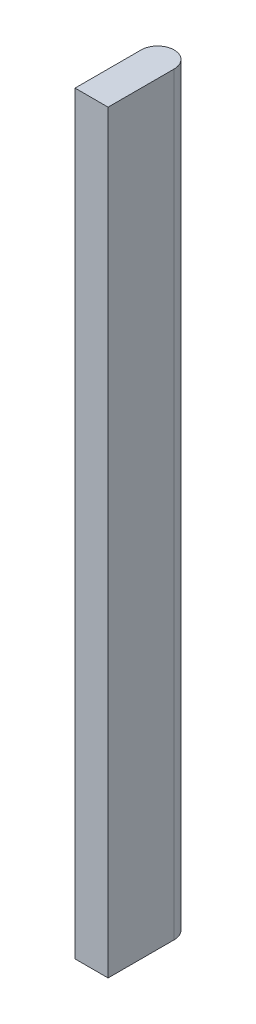
SolidWorks part; units mm, degrees
material "Delrin 2700 NC010, Low Viscosity Acetal Copolymer (SS)"
ref_plane "Front Plane" through (0, 0, 0) normal (0, 0, 1) x (1, 0, 0)
ref_plane "Top Plane" through (0, 0, 0) normal (0, 1, 0) x (1, 0, 0)
ref_plane "Right Plane" through (0, 0, 0) normal (1, 0, 0) x (0, 0, -1)
sketch "Sketch1" plane through (0, 0, 0) normal (0, 1, 0) x (1, 0, 0)
  line L1 (0, 0) -> (6.35, 0)
  line L2 (0, 0) -> (0, 12.705)
  line L3 (3.17, 15.875) -> (3.18, 15.875)
  line L4 (6.35, 0) -> (6.35, 12.705)
  arc A0 (0, 12.705) -> (3.17, 15.875) centre (3.17, 12.705) cw
  arc A1 (3.18, 15.875) -> (6.35, 12.705) centre (3.18, 12.705) cw
  point P9 (0, 15.875)
  point P12 (6.35, 15.875)
  dimension "D3" = 3.17
  dimension "D1" = 15.875
  dimension "D2" = 6.35
extrude "Boss-Extrude1" add sketch "Sketch1" along normal blind 145
